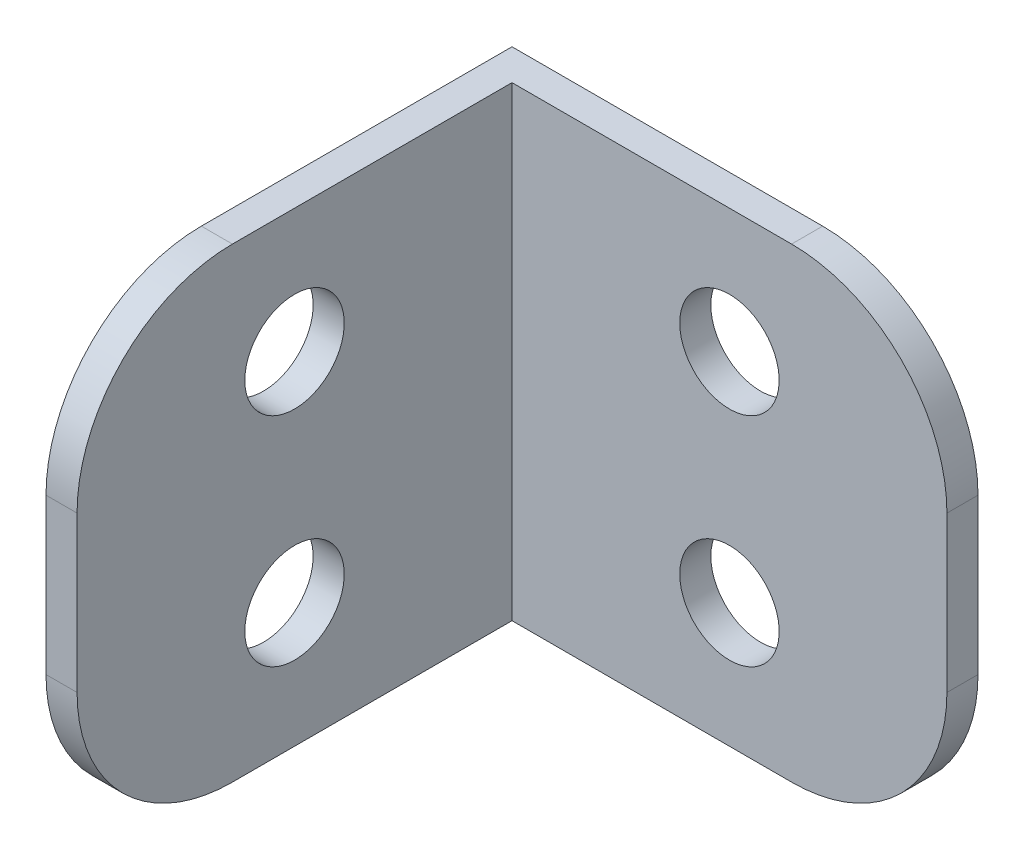
SolidWorks part; units mm, degrees
ref_plane "前视基准面" through (0, 0, 0) normal (0, 0, 1) x (1, 0, 0)
ref_plane "上视基准面" through (0, 0, 0) normal (0, 1, 0) x (1, 0, 0)
ref_plane "右视基准面" through (0, 0, 0) normal (1, 0, 0) x (0, 0, -1)
other "Configuration Table"
sketch "草图1" plane through (0, 0, 0) normal (0, 1, 0) x (1, 0, 0)
  line L0 (0, 0) -> (-15, 0)
  line L1 (-15, 0) -> (-15, -15)
  line L2 (-15, -15) -> (-14, -15)
  line L3 (-14, -15) -> (-14, -1)
  line L4 (-14, -1) -> (0, -1)
  line L5 (0, -1) -> (0, 0)
  dimension "D1" = 1
  dimension "D2" = 1
  dimension "D3" = 15
  dimension "D4" = 15
extrude "凸台-拉伸1" add sketch "草图1" along normal blind 15
fillet "圆角1" radius 5 4 edges at (-14.5, 15, 15) (-14.5, 0, 15) (0, 0, 0.5) (0, 15, 0.5)
sketch "草图2" plane through (0, 0, 0) normal (0, 0, -1) x (-1, 0, 0)
  line L0 (5, 0) -> (15, 0) construction
  line L1 (5, 15) -> (15, 15) construction
  line L2 (15, 15) -> (15, 0) construction
  circle A0 centre (7, 11) radius 1.6
  circle A1 centre (7, 4) radius 1.6
  dimension "D1" = 3.2
  dimension "D2" = 3.2
  dimension "D3" = 4
  dimension "D4" = 4
  dimension "D5" = 8
  dimension "D6" = 8
extrude "切除-拉伸1" cut sketch "草图2" against normal blind 15
sketch "草图3" plane through (-15, 0, 0) normal (-1, 0, 0) x (0, 0, 1)
  line L0 (0, 15) -> (0, 0) construction
  line L1 (0, 15) -> (10, 15) construction
  line L2 (0, 0) -> (10, 0) construction
  circle A0 centre (8, 11) radius 1.6
  circle A1 centre (8, 4) radius 1.6
  dimension "D1" = 3.2
  dimension "D2" = 3.2
  dimension "D3" = 8
  dimension "D4" = 4
  dimension "D5" = 4
  dimension "D6" = 8
extrude "切除-拉伸2" cut sketch "草图3" against normal blind 15
